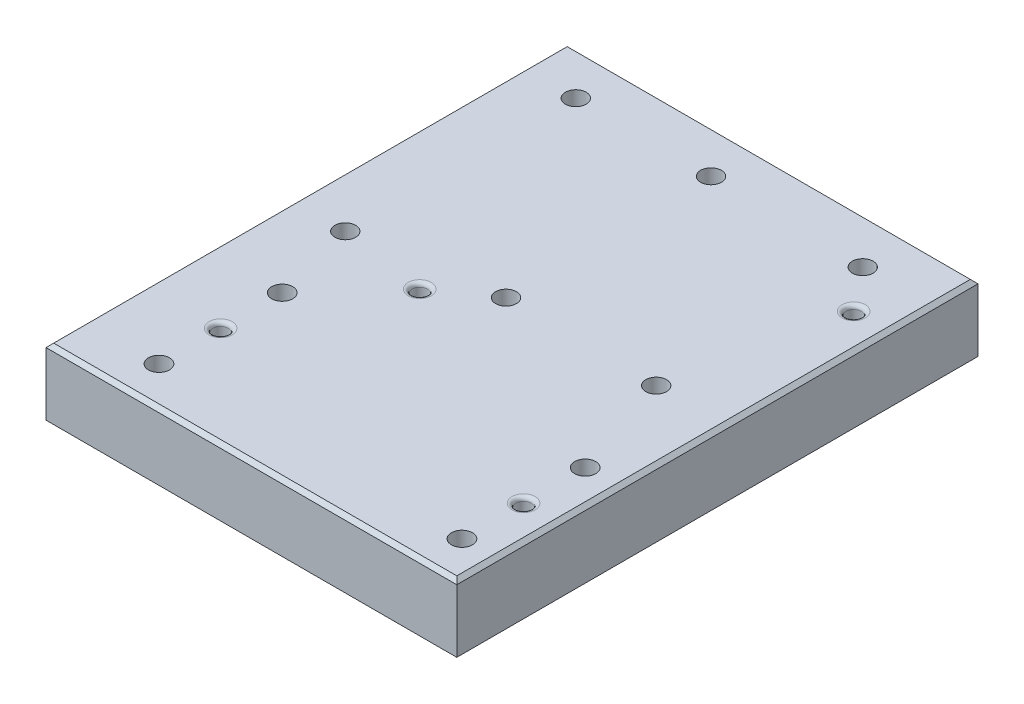
SolidWorks part; units mm, degrees
material "201.0-T6 Insulated Mold Casting (SS)"
ref_plane "Front Plane" through (0, 0, 0) normal (0, 0, 1) x (1, 0, 0)
ref_plane "Top Plane" through (0, 0, 0) normal (0, 1, 0) x (1, 0, 0)
ref_plane "Right Plane" through (0, 0, 0) normal (1, 0, 0) x (0, 0, -1)
sketch "Sketch1" plane through (0, 0, 0) normal (0, 1, 0) x (1, 0, 0)
  line L0 (-4.5658, -10) -> (155.4342, -10) construction
  line L1 (-4.5658, -58) -> (155.4342, -58) construction
  line L2 (29.4342, -10) -> (29.4342, -58) construction
  line L3 (0.4342, 130) -> (160.4342, 130)
  line L4 (5, 5) -> (5, 125) construction
  line L5 (147.4342, -10) -> (147.4342, -58) construction
  line L6 (5, 5) -> (250, 5) construction
  line L7 (-4.5658, 5) -> (155.4342, 5) construction
  line L8 (88.4342, 130) -> (88.4342, -73) construction
  line L9 (0, 0) -> (255, 0) construction
  line L10 (29.4342, -34) -> (147.4342, -34) construction
  line L11 (21, 112.78) -> (73.68, 112.78) construction
  line L12 (160.4342, 130) -> (160.4342, -73)
  line L13 (-4.5658, 130) -> (-4.5658, -73) construction
  line L14 (0.4342, 130) -> (0.4342, -73)
  line L15 (0, 130) -> (255, 130) construction
  line L16 (5, 125) -> (250, 125) construction
  line L21 (21.4342, 130) -> (21.4342, -73) construction
  line L22 (0.4342, -73) -> (160.4342, -73)
  line L23 (155.4342, 130) -> (155.4342, -73) construction
  line L24 (250, 5) -> (250, 125) construction
  line L25 (255, 0) -> (255, 130) construction
  line L26 (0, 0) -> (0, 130) construction
  circle A0 centre (73.68, 112.78) radius 4.05
  circle A1 centre (133.87, 111.67) radius 4.05
  circle A2 centre (133.61, 31.48) radius 4.05
  circle A3 centre (74.69, 31.92) radius 4.05
  circle A4 centre (29.4342, -10) radius 4.1
  circle A5 centre (29.4342, -58) radius 4.1
  circle A6 centre (21, 112.78) radius 4.05
  circle A7 centre (147.4342, -58) radius 4.1
  circle A8 centre (147.4342, -10) radius 4.1
  circle A9 centre (21, 23) radius 4.05
  circle A10 centre (29.4342, -34) radius 3
  circle A11 centre (147.4342, -34) radius 3
  circle A12 centre (147, 95) radius 3
  circle A13 centre (55, 18) radius 3
  point P43 (25, 136.0866)
  point P44 (25, -5.597)
  dimension "D5" = 8.1
  dimension "D6" = 8.1
  dimension "D7" = 8.1
  dimension "D8" = 8.1
  dimension "D16" = 104.92
  dimension "D17" = 185.78
  dimension "D23" = 152
  dimension "D24" = 8.1
  dimension "D25" = 25.5658
  dimension "D26" = 8.1
  dimension "D28" = 59.5658
  dimension "D32" = 151.5658
  dimension "D33" = 6
  dimension "D31" = 138.4358
  dimension "D39" = 6
  dimension "D13" = 6
  dimension "D12" = 8.2
  dimension "D1" = 203
  dimension "D9" = 15
  dimension "D10" = 39
  dimension "D11" = 134
  dimension "D14" = 91
  dimension "D15" = 96
  dimension "D18" = 63
  dimension "D19" = 104.48
  dimension "D20" = 168
  dimension "D21" = 184.67
  dimension "D22" = 34
  dimension "D27" = 78.2458
  dimension "D29" = 79.2558
  dimension "D34" = 5
  dimension "D35" = 5
  dimension "D30" = 138.1758
  dimension "D40" = 160
extrude "Boss-Extrude1" add sketch "Sketch1" along normal blind 26
fillet "Fillet1" radius 1.5 4 edges at (147.4342, 26, 37) (29.4342, 26, 37) (55, 26, -15) (147, 26, -92)
chamfer "Chamfer1" distance 1.5 angle 45 4 edges at (80.4342, 26, 73) (160.4342, 26, -28.5) (0.4342, 26, -28.5) (80.4342, 26, -130)
